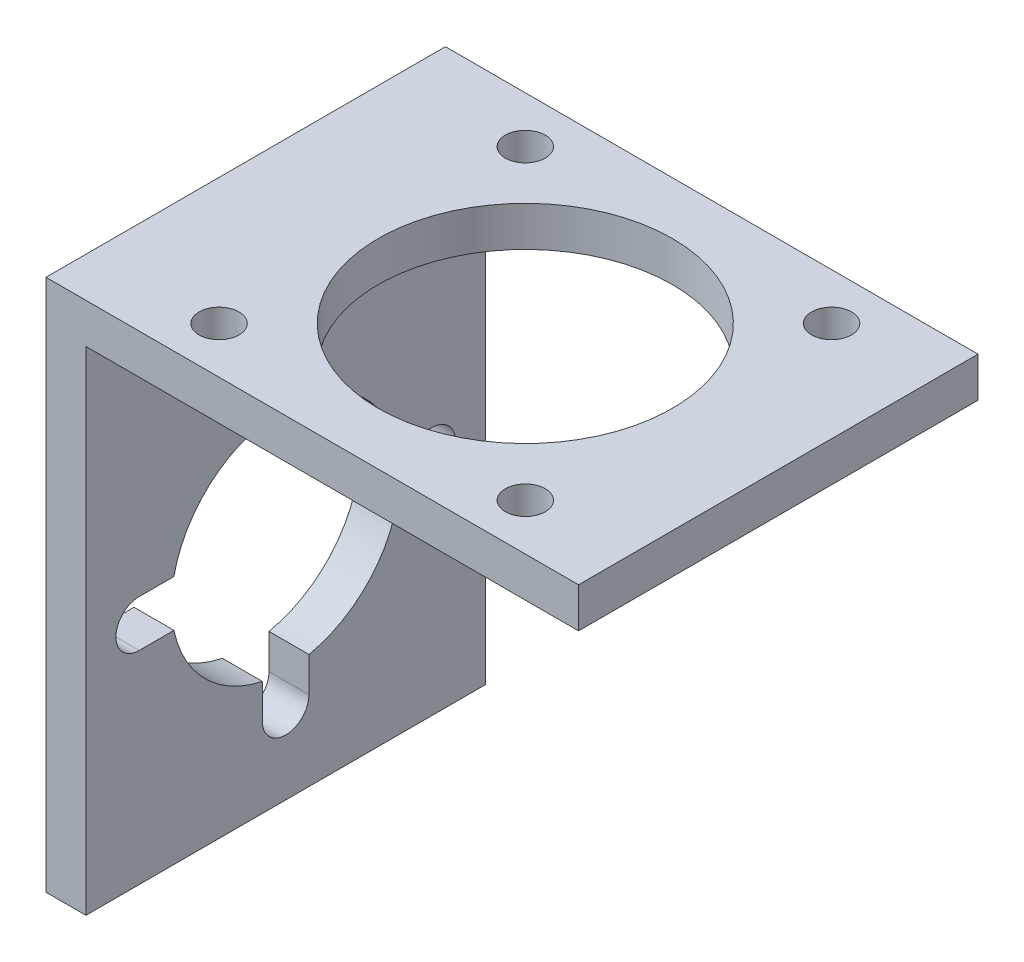
SolidWorks part; units mm, degrees
material "6061 Alloy"
ref_plane "Front" through (0, 0, 0) normal (0, 0, 1) x (1, 0, 0)
ref_plane "Top" through (0, 0, 0) normal (0, 1, 0) x (1, 0, 0)
ref_plane "Right" through (0, 0, 0) normal (1, 0, 0) x (0, 0, -1)
ref_plane "Plane1" through (0, 0, 30) normal (0, 0, 1) x (1, 0, 0)
sketch "Sketch1" plane through (0, 0, 30) normal (0, 0, 1) x (1, 0, 0)
  line L0 (40, -40) -> (40, 0)
  line L1 (40, 0) -> (0, 0)
  line L2 (0, 0) -> (0, -40)
  line L3 (0, -40) -> (40, -40)
extrude "Boss-Extrude1" add sketch "Sketch1" against normal blind 30
sketch "Sketch2" plane through (0, 0, 0) normal (0, 0, -1) x (-1, 0, 0)
  line L0 (-3, -40) -> (-3, -3)
  line L1 (-3, -3) -> (-40, -3)
  line L2 (-40, -3) -> (-40, -40)
  line L3 (-40, -40) -> (-3, -40)
extrude "Cut-Extrude1" cut sketch "Sketch2" against normal through all
sketch "Sketch3" plane through (0, 0, 0) normal (-1, 0, 0) x (0, 0, 1)
  line L0 (13.25, -12.02) -> (13.25, -14.6306)
  line L1 (6.6106, -21.27) -> (4, -21.27)
  line L2 (4, -24.77) -> (6.6106, -24.77)
  line L3 (13.25, -31.4094) -> (13.25, -34.02)
  line L4 (16.75, -34.02) -> (16.75, -31.4094)
  line L5 (23.3894, -24.77) -> (26, -24.77)
  line L6 (26, -21.27) -> (23.3894, -21.27)
  line L7 (16.75, -14.6306) -> (16.75, -12.02)
  arc A0 (16.75, -12.02) -> (13.25, -12.02) centre (15, -12.02) ccw
  arc A1 (13.25, -14.6306) -> (6.6106, -21.27) centre (15, -23.02) ccw
  arc A2 (4, -21.27) -> (4, -24.77) centre (4, -23.02) ccw
  arc A3 (6.6106, -24.77) -> (13.25, -31.4094) centre (15, -23.02) ccw
  arc A4 (13.25, -34.02) -> (16.75, -34.02) centre (15, -34.02) ccw
  arc A5 (16.75, -31.4094) -> (23.3894, -24.77) centre (15, -23.02) ccw
  arc A6 (26, -24.77) -> (26, -21.27) centre (26, -23.02) ccw
  arc A7 (23.3894, -21.27) -> (16.75, -14.6306) centre (15, -23.02) ccw
extrude "Cut-Extrude2" cut sketch "Sketch3" against normal through all
hole_wizard "Hole1" positions "Sketch5" profile "Sketch4" legacy
sketch "Sketch5" plane through (0, -3, 0) normal (0, -1, 0) x (-1, 0, 0)
  point P0 (-21, -15)
sketch "Sketch4" plane through (21, -3, 15) normal (1, 0, 0) x (0, 0, -1)
  line L0 (0, 0) -> (0, 3)
  line L1 (0, 3) -> (11.05, 3)
  line L2 (11.05, 3) -> (11.05, 0)
  line L3 (11.05, 0) -> (0, 0)
  line L4 (0, 110) -> (0, -10) construction
  dimension "Diameter" = 22.1
  dimension "Depth" = 3
hole_wizard "#3 Clearance Hole1" positions "Sketch7" profile "Sketch6" hole size "#3" standard "ANSI Inch"
sketch "Sketch7" plane through (0, -3, 0) normal (0, -1, 0) x (-1, 0, 0)
  point P0 (-9.5, -26.5022)
  point P1 (-9.4978, -3.5)
  point P2 (-32.5, -3.4978)
  point P3 (-32.5022, -26.5)
sketch "Sketch6" plane through (9.5, -3, 26.5022) normal (1, 0, 0) x (0, 0, -1)
  line L0 (0, 0) -> (0, 3)
  line L1 (0, 3) -> (1.5, 3)
  line L2 (1.5, 3) -> (1.5, 0)
  line L5 (1.5, 0) -> (0, 0)
  line L11 (0, -6.35) -> (0, 107.95) construction
  dimension "Thru Hole Dia." = 3
  dimension "Thru Hole Depth" = 3
